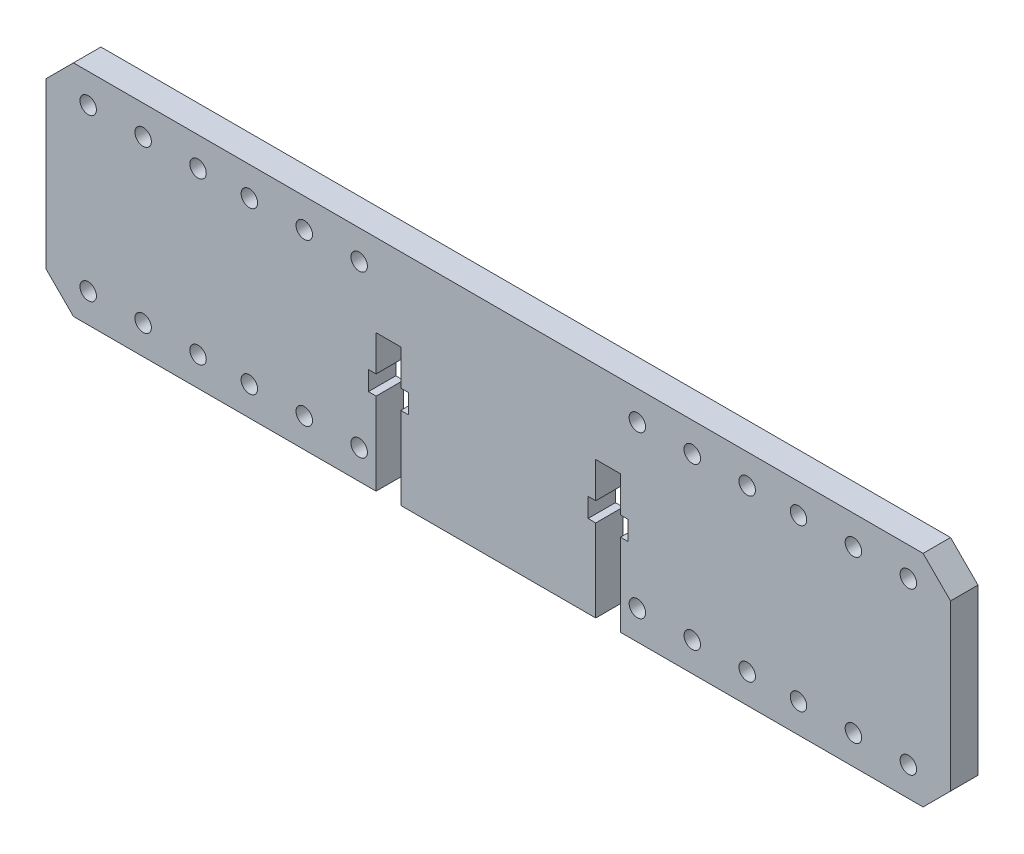
SolidWorks part; units mm, degrees
ref_plane "前视基准面" through (0, 0, 0) normal (0, 0, 1) x (1, 0, 0)
ref_plane "上视基准面" through (0, 0, 0) normal (0, 1, 0) x (1, 0, 0)
ref_plane "右视基准面" through (0, 0, 0) normal (1, 0, 0) x (0, 0, -1)
sketch "草图1" plane through (0, 0, 0) normal (0, 0, 1) x (1, 0, 0)
  line L0 (-86.0937, -20) -> (-22.25, -20) construction
  line L1 (-82.3563, -20) -> (-22.25, -20)
  line L2 (-64.6725, 14.6725) -> (-35.3275, -14.6725) construction
  line L3 (-64.6725, 14.6725) -> (-35.3275, 14.6725) construction
  line L6 (-35.3275, 14.6725) -> (-35.3275, -14.6725) construction
  line L7 (-35.3275, 14.6725) -> (-64.6725, -14.6725) construction
  line L8 (0, 31.5835) -> (0, -35.5842) construction
  line L9 (-22.25, -20) -> (-22.25, -5)
  line L10 (-22.25, -5) -> (-23.65, -5)
  line L11 (-23.65, -5) -> (-23.65, -1.5)
  line L12 (-23.65, -1.5) -> (-22.25, -1.5)
  line L13 (-22.25, -1.5) -> (-22.25, 5)
  line L14 (-22.25, 5) -> (-17.75, 5)
  line L15 (-20, -2.2965) -> (-20, -23.0981) construction
  line L16 (-17.75, -20) -> (-17.75, -5)
  line L17 (-17.75, -5) -> (-16.35, -5)
  line L18 (-16.35, -5) -> (-16.35, -1.5)
  line L19 (-16.35, -1.5) -> (-17.75, -1.5)
  line L20 (-17.75, -1.5) -> (-17.75, 5)
  line L21 (23.65, -1.5) -> (22.25, -1.5)
  line L22 (23.65, -5) -> (23.65, -1.5)
  line L23 (22.25, -5) -> (23.65, -5)
  line L24 (22.25, -20) -> (22.25, -5)
  line L25 (17.75, -5) -> (16.35, -5)
  line L26 (17.75, -20) -> (17.75, -5)
  line L27 (16.35, -5) -> (16.35, -1.5)
  line L28 (16.35, -1.5) -> (17.75, -1.5)
  line L29 (22.25, 5) -> (17.75, 5)
  line L30 (17.75, -1.5) -> (17.75, 5)
  line L31 (22.25, -1.5) -> (22.25, 5)
  line L32 (-17.75, -20) -> (17.75, -20) construction
  line L33 (-17.75, -20) -> (17.75, -20)
  line L34 (22.25, -20) -> (95.0067, -20) construction
  line L35 (22.25, -20) -> (82.3563, -20)
  line L36 (-82.3563, -20) -> (-82.3563, 20)
  line L37 (-82.3563, 20) -> (82.3563, 20)
  line L38 (82.3563, 20) -> (82.3563, -20)
  circle A1 centre (-64.6725, 14.6725) radius 1.5
  circle A2 centre (-35.3275, 14.6725) radius 1.5
  circle A3 centre (-64.6725, -14.6725) radius 1.5
  circle A4 centre (-35.3275, -14.6725) radius 1.5
  circle A5 centre (64.6725, 14.6725) radius 1.5
  circle A6 centre (64.6725, -14.6725) radius 1.5
  circle A7 centre (35.3275, -14.6725) radius 1.5
  circle A8 centre (35.3275, 14.6725) radius 1.5
  circle A9 centre (-54.6725, 14.6725) radius 1.5
  circle A10 centre (-25.3275, 14.6725) radius 1.5
  circle A11 centre (-54.6725, -14.6725) radius 1.5
  circle A12 centre (-25.3275, -14.6725) radius 1.5
  circle A13 centre (-74.6725, 14.6725) radius 1.5
  circle A14 centre (-45.3275, 14.6725) radius 1.5
  circle A15 centre (-45.3275, -14.6725) radius 1.5
  circle A16 centre (-74.6725, -14.6725) radius 1.5
  circle A17 centre (45.3275, 14.6725) radius 1.5
  circle A18 centre (45.3275, -14.6725) radius 1.5
  circle A19 centre (74.6725, -14.6725) radius 1.5
  circle A20 centre (74.6725, 14.6725) radius 1.5
  circle A21 centre (25.3275, 14.6725) radius 1.5
  circle A22 centre (25.3275, -14.6725) radius 1.5
  circle A23 centre (54.6725, -14.6725) radius 1.5
  circle A24 centre (54.6725, 14.6725) radius 1.5
  point P10 (-50, 0)
  point P40 (-20, 5)
  dimension "D6" = 3
  dimension "D7" = 3
  dimension "D8" = 3
  dimension "D9" = 3
  dimension "D17" = 20.75
  dimension "D3" = 20.75
  dimension "D18" = 20.75
  dimension "D19" = 5.3275
  dimension "D4" = 20.75
  dimension "D22" = 2
  dimension "D10" = 7.3
  dimension "D11" = 3.5
  dimension "D12" = 4.5
  dimension "D13" = 4.5
  dimension "D14" = 25
  dimension "D15" = 15
  dimension "D16" = 20
  dimension "D20" = 20
  dimension "D21" = 2
  dimension "D23" = 2
  dimension "D24" = 2
extrude "凸台-拉伸1" add sketch "草图1" along normal blind 5
chamfer "倒角1" distance 5 angle 45 4 edges at (-82.3563, 20, 2.5) (82.3563, -20, 2.5) (82.3563, 20, 2.5) (-82.3563, -20, 2.5)
